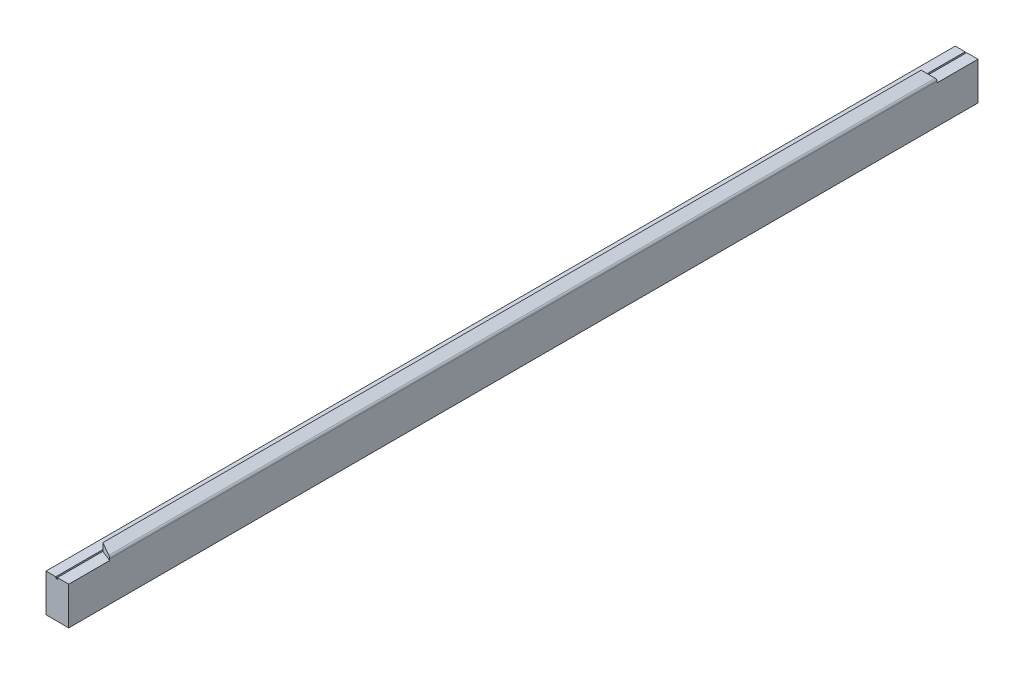
SolidWorks part; units mm, degrees
ref_plane "Plan de face" through (0, 0, 0) normal (0, 0, 1) x (1, 0, 0)
ref_plane "Plan de dessus" through (0, 0, 0) normal (0, 1, 0) x (1, 0, 0)
ref_plane "Plan de droite" through (0, 0, 0) normal (1, 0, 0) x (0, 0, -1)
sketch "Esquisse1" plane through (0, 0, 0) normal (0, 0, 1) x (1, 0, 0)
  line L1 (0, 0) -> (30, 0)
  line L2 (0, 0) -> (0, 60)
  line L3 (0, 60) -> (30, 60)
  line L4 (30, 0) -> (30, 60)
  dimension "D1" = 30
  dimension "D2" = 60
extrude "Boss.-Extru.1" add sketch "Esquisse1" along normal blind 1200
sketch "Esquisse2" plane through (0, 0, 1200) normal (0, 0, 1) x (1, 0, 0)
  line L0 (0, 0) -> (30, 0) construction
  line L1 (20, 0) -> (30, 0)
  line L2 (20, 0) -> (20, 10)
  line L3 (20, 10) -> (30, 10)
  line L4 (30, 0) -> (30, 10)
  line L5 (30, 0) -> (30, 60) construction
  dimension "D1" = 10
  dimension "D2" = 10
extrude "Enlèv. mat.-Extru.1" [suppressed] cut sketch "Esquisse2" against normal through all both and the other way through all
sketch "Esquisse5" plane through (0, 0, 1200) normal (0, 0, 1) x (1, 0, 0)
  line L0 (0, 0) -> (30, 0) construction
  line L1 (0, 60) -> (15, 60)
  line L2 (0, 60) -> (0, 50)
  line L3 (0, 50) -> (15, 50)
  line L4 (15, 60) -> (15, 50)
  dimension "D1" = 50
  dimension "D2" = 15
extrude "Enlèv. mat.-Extru.4" cut sketch "Esquisse5" against normal through all both and the other way through all
sketch "Esquisse3" plane through (0, 0, 1200) normal (0, 0, 1) x (1, 0, 0)
  line L0 (15, 60) -> (30, 54)
  line L1 (30, 0) -> (30, 60) construction
  line L2 (30, 54) -> (30, 60)
  line L3 (30, 60) -> (15, 60)
  line L4 (15, 60) -> (15, 50) construction
  line L5 (30, 60) -> (15, 60) construction
  dimension "D1" = 6
extrude "Enlèv. mat.-Extru.2" cut sketch "Esquisse3" against normal through all both and the other way through all
sketch "Esquisse4" [suppressed] plane through (0, 0, 1200) normal (0, 0, 1) x (1, 0, 0)
  line L0 (20, 10) -> (30, 10) construction
  line L1 (27.5, 10) -> (22.5, 10)
  arc A0 (22.5, 10) -> (27.5, 10) centre (25, 10) cw
  dimension "D1" = 5
extrude "Enlèv. mat.-Extru.3" [suppressed] cut sketch "Esquisse4" against normal through all both and the other way through all
fillet "Congé1" radius 3 1 edges at (30, 54, 600)
sketch "Esquisse6" plane through (0, 50, 0) normal (0, 1, 0) x (1, 0, 0)
  line L0 (30, 0) -> (30, -1200) construction
  line L1 (0, -1200) -> (30, -1200)
  line L2 (30, -1146) -> (15, -1140)
  line L3 (15, 0) -> (15, -1200) construction
  line L4 (30, -1200) -> (30, -1146)
  line L5 (0, -600) -> (61.2122, -600) construction
  line L6 (0, 0) -> (0, -1200) construction
  line L7 (0, -60) -> (0, 0)
  line L8 (15, -60) -> (0, -60)
  line L9 (30, 0) -> (30, -54)
  line L10 (30, -54) -> (15, -60)
  line L11 (15, -1140) -> (0, -1140)
  line L12 (0, -1140) -> (0, -1200)
  line L13 (0, 0) -> (30, 0)
  dimension "D1" = 60
  dimension "D2" = 6
extrude "Enlèv. mat.-Extru.5" cut sketch "Esquisse6" along normal up to vertex up to point (15, 60, 1200)
fillet "Congé2" [suppressed] radius 3
sketch "Esquisse7" plane through (0, 50, 0) normal (0, 1, 0) x (1, 0, 0)
  line L0 (30, -1200) -> (0, -1200) construction
  line L1 (13, -1200) -> (15, -1200)
  line L2 (13, -1200) -> (13, 0)
  line L3 (13, 0) -> (15, 0)
  line L4 (15, -1200) -> (15, 0)
  line L5 (0, 0) -> (30, 0) construction
  line L6 (15, -60) -> (15, -1140) construction
  dimension "D1" = 2
extrude "Enlèv. mat.-Extru.6" cut sketch "Esquisse7" against normal blind 2
